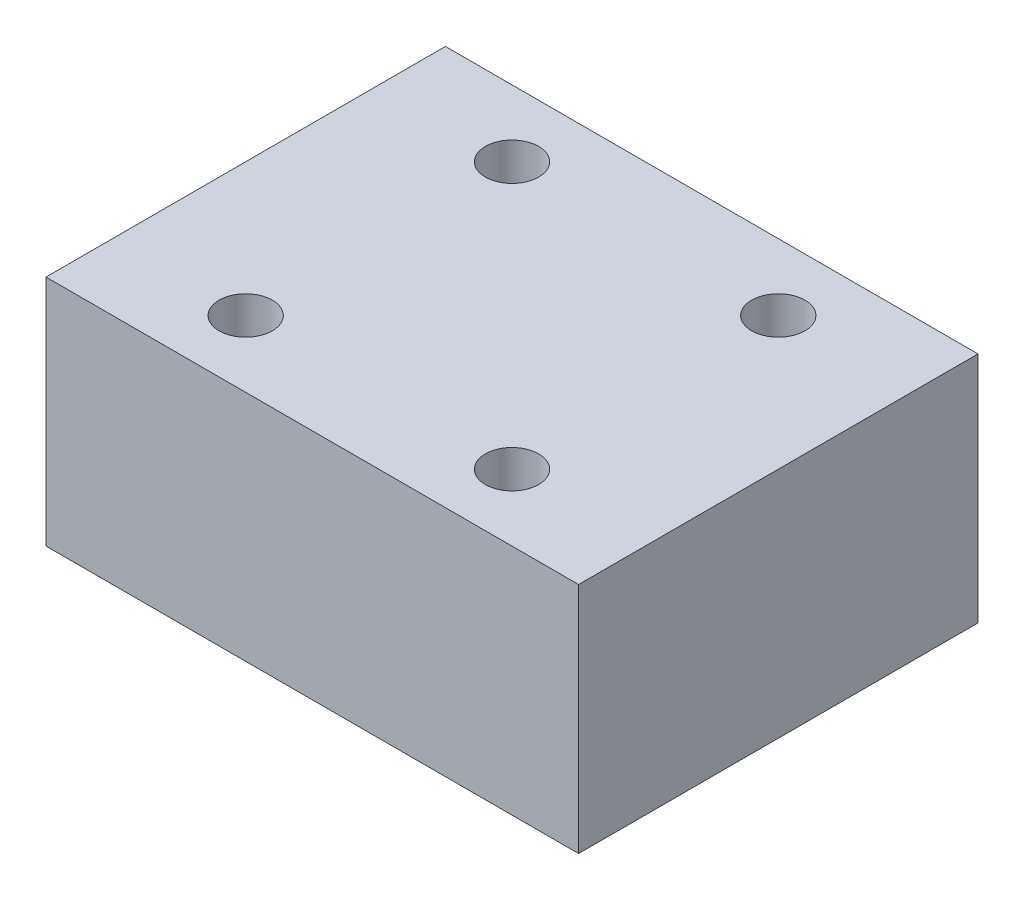
SolidWorks part; units mm, degrees
ref_plane "Front Plane" through (0, 0, 0) normal (0, 0, 1) x (1, 0, 0)
ref_plane "Top Plane" through (0, 0, 0) normal (0, 1, 0) x (1, 0, 0)
ref_plane "Right Plane" through (0, 0, 0) normal (1, 0, 0) x (0, 0, -1)
sketch "Sketch1" plane through (0, 0, 0) normal (0, 0, 1) x (1, 0, 0)
  line L1 (50.8, 22.225) -> (-50.8, 22.225)
  line L2 (50.8, 22.225) -> (50.8, -22.225)
  line L3 (50.8, -22.225) -> (-50.8, -22.225)
  line L4 (-50.8, 22.225) -> (-50.8, -22.225)
  line L5 (50.8, 22.225) -> (-50.8, -22.225) construction
  line L6 (50.8, -22.225) -> (-50.8, 22.225) construction
  point P0 (0, 0)
  dimension "D1" = 101.6
  dimension "D2" = 44.45
extrude "Boss-Extrude1" add sketch "Sketch1" along normal mid plane 76.2
sketch "Sketch2" plane through (0, 22.225, 0) normal (0, 1, 0) x (1, 0, 0)
  line L1 (25.4, -25.4) -> (-25.4, -25.4)
  line L2 (25.4, -25.4) -> (25.4, 25.4)
  line L3 (25.4, 25.4) -> (-25.4, 25.4)
  line L4 (-25.4, -25.4) -> (-25.4, 25.4)
  line L5 (25.4, -25.4) -> (-25.4, 25.4) construction
  line L6 (25.4, 25.4) -> (-25.4, -25.4) construction
  point P0 (0, 0)
  dimension "D1" = 50.8
  dimension "D2" = 50.8
hole_wizard "0.4in diameter hole" positions "Sketch3" profile "Sketch4" hole size "#97" standard "ANSI Inch" end condition through all
sketch "Sketch3" plane through (0, 22.225, 0) normal (0, 1, 0) x (1, 0, 0)
  point P0 (-25.4, 25.4)
  point P3 (-25.4, -25.4)
  point P6 (25.4, -25.4)
  point P9 (25.4, 25.4)
sketch "Sketch4" plane through (-25.4, 22.225, -25.4) normal (1, 0, 0) x (0, 0, 1)
  line L0 (0, 0) -> (0, 44.45)
  line L1 (0, 44.45) -> (5.08, 44.45)
  line L2 (5.08, 44.45) -> (5.08, 0)
  line L5 (5.08, 0) -> (0, 0)
  line L11 (0, -6.35) -> (0, 107.95) construction
  dimension "Thru Hole Dia." = 10.16
  dimension "Thru Hole Depth" = 44.45
